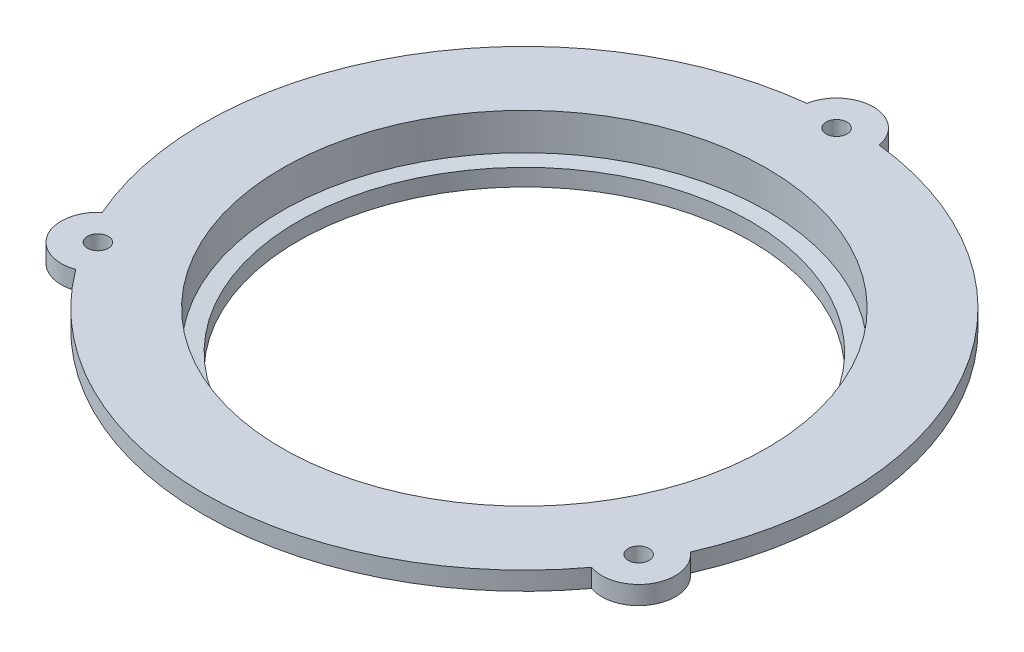
SolidWorks part; units mm, degrees
ref_plane "Plan de face" through (0, 0, 0) normal (0, 0, 1) x (1, 0, 0)
ref_plane "Plan de dessus" through (0, 0, 0) normal (0, 1, 0) x (1, 0, 0)
ref_plane "Plan de droite" through (0, 0, 0) normal (1, 0, 0) x (0, 0, -1)
sketch "Esquisse1" plane through (0, 0, 0) normal (0, 0, 1) x (1, 0, 0)
  line L0 (0, 0) -> (0, 7.4302) construction
  line L2 (-39.6, 5.1329) -> (-39.6, -0.8671)
  line L3 (-39.6, 5.1329) -> (-52.4, 5.1329)
  line L4 (-52.4, 5.1329) -> (-52.4, 2.1329)
  line L5 (-52.4, 2.1329) -> (-47.4, 2.1329)
  line L6 (-47.4, 2.1329) -> (-47.4, -0.8671)
  line L10 (-47.4, -0.8671) -> (-42, -3.8671)
  line L11 (-42, -3.8671) -> (-37, -3.8671)
  line L12 (-37, -3.8671) -> (-37, -1.0918)
  arc A1 (-37, -1.0918) -> (-39.6, -0.8671) centre (-23.7384, 167.558) cw
  dimension "D2" = 9
  dimension "D1" = 3
  dimension "D3" = 5
  dimension "D4" = 47.4
  dimension "D5" = 39.6
  dimension "D6" = 3
  dimension "D7" = 6
  dimension "D8" = 5
  dimension "D9" = 37
revolve "Révolution1" add sketch "Esquisse1" angle 360 about L0
sketch "Esquisse2" plane through (0, 5.1329, 0) normal (0, 1, 0) x (1, 0, 0)
  line L0 (0, 0) -> (0, 89.8813) construction
  line L1 (-5.9045, 52.0663) -> (0, 51)
  line L2 (0, 51) -> (5.9045, 52.0663)
  arc A0 (-5.9045, 52.0663) -> (5.9045, 52.0663) centre (0, 51) cw
  circle A1 centre (0, 0) radius 52.4 construction
  dimension "D2" = 6
  dimension "D1" = 51
extrude "Boss.-Extru.2" add sketch "Esquisse2" against normal blind 3 contours A0 L2 L1
hole_wizard "Dégagement M32" positions "Esquisse7" profile "Esquisse6" hole size "M3" standard "ISO" end condition through all
sketch "Esquisse7" plane through (0, 5.1329, 0) normal (0, 1, 0) x (1, 0, 0)
  point P0 (0, 51)
sketch "Esquisse6" plane through (0, 5.1329, -51) normal (1, 0, 0) x (0, 0, 1)
  line L0 (0, 0) -> (0, 9)
  line L1 (0, 9) -> (1.7, 9)
  line L2 (1.7, 9) -> (1.7, 0)
  line L5 (1.7, 0) -> (0, 0)
  line L11 (0, -6.35) -> (0, 107.95) construction
  dimension "Diamètre du perçage jusqu'au prochain" = 3.4
  dimension "Profondeur du perçage jusqu'au prochain" = 9
pattern_circular "Répétition circulaire1" count 3 every 120 about axis through (0, 0, 0) along (0, 1, 0) of "Boss.-Extru.2", "Dégagement M32"
